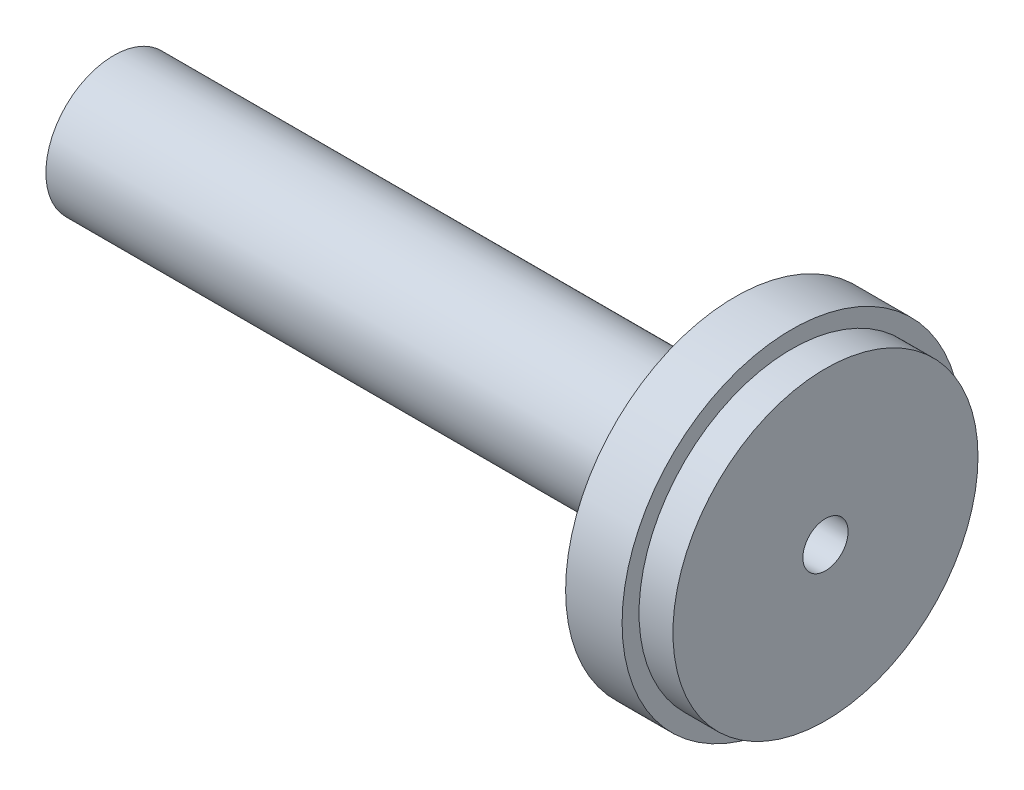
SolidWorks part; units mm, degrees
ref_plane "Front Plane" through (0, 0, 0) normal (0, 0, 1) x (1, 0, 0)
ref_plane "Top Plane" through (0, 0, 0) normal (0, 1, 0) x (1, 0, 0)
ref_plane "Right Plane" through (0, 0, 0) normal (1, 0, 0) x (0, 0, -1)
sketch "Sketch1" plane through (0, 0, 0) normal (0, 0, 1) x (1, 0, 0)
  line L0 (-61.1123, 0) -> (-61.1123, 2)
  line L1 (-61.1123, 2) -> (-6.1123, 2)
  line L2 (-6.1123, 2) -> (-6.1123, 11)
  line L3 (-6.1123, 11) -> (-1.1123, 11)
  line L4 (-1.1123, 11) -> (-1.1123, 9.5)
  line L5 (-1.1123, 9.5) -> (1.8877, 9.5)
  line L6 (1.8877, 9.5) -> (1.8877, -2)
  line L7 (1.8877, -2) -> (-61.1123, 0)
  line L8 (1.8877, -4) -> (-10.5731, -4)
revolve "Revolve1" add sketch "Sketch1" angle 360 about L8
